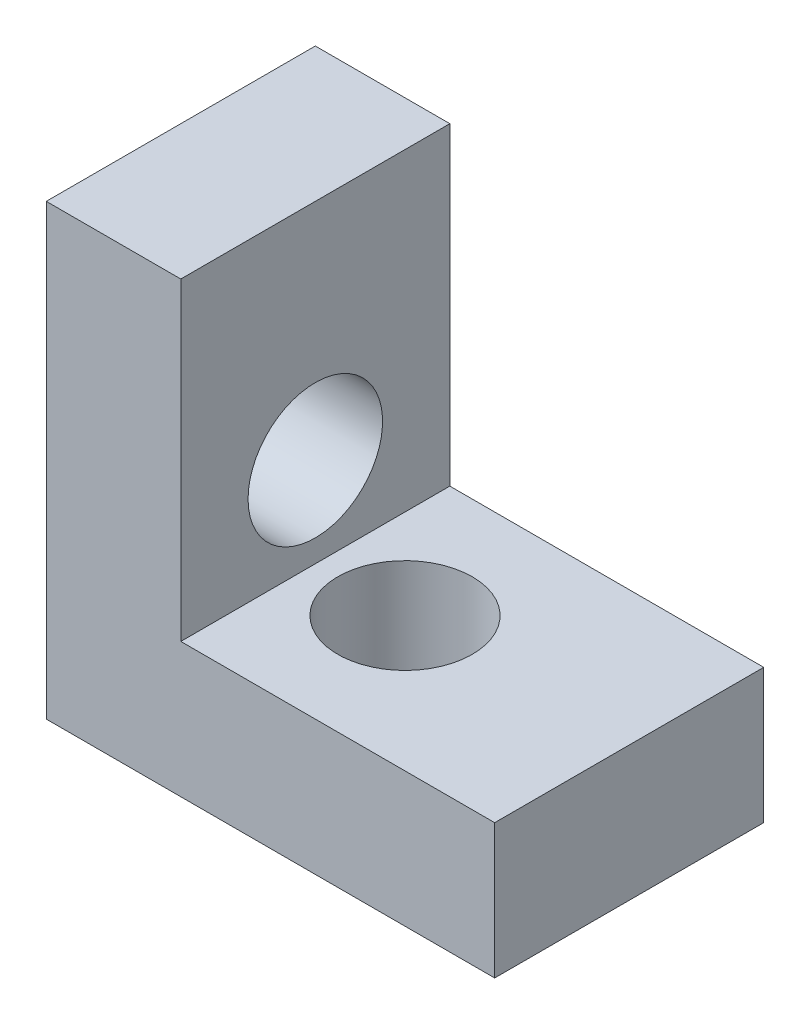
SolidWorks part; units mm, degrees
ref_plane "前视基准面" through (0, 0, 0) normal (0, 0, 1) x (1, 0, 0)
ref_plane "上视基准面" through (0, 0, 0) normal (0, 1, 0) x (1, 0, 0)
ref_plane "右视基准面" through (0, 0, 0) normal (1, 0, 0) x (0, 0, -1)
other "Configuration Table"
sketch "草图1" plane through (0, 0, 0) normal (0, 1, 0) x (1, 0, 0)
  line L1 (-5, -3) -> (5, -3)
  line L2 (-5, -3) -> (-5, 3)
  line L3 (-5, 3) -> (5, 3)
  line L4 (5, -3) -> (5, 3)
  line L5 (-5, -3) -> (5, 3) construction
  line L6 (-5, 3) -> (5, -3) construction
  point P0 (0, 0)
  dimension "D1" = 6
  dimension "D2" = 10
extrude "凸台-拉伸1" add sketch "草图1" along normal blind 3
sketch "草图2" plane through (0, 3, 0) normal (0, 1, 0) x (1, 0, 0)
  line L0 (-5, -3) -> (5, -3) construction
  line L1 (-5, 3) -> (-2, 3)
  line L2 (-5, 3) -> (-5, -3)
  line L3 (-5, -3) -> (-2, -3)
  line L4 (-2, 3) -> (-2, -3)
  dimension "D1" = 3
extrude "凸台-拉伸2" add sketch "草图2" along normal blind 7
sketch "草图3" plane through (0, 0, 0) normal (0, -1, 0) x (1, 0, 0)
  line L4 (5, -3) -> (5, 3)
  line L5 (5, 3) -> (-5, 3)
  line L6 (-5, 3) -> (-5, -3)
  line L7 (-5, -3) -> (5, -3)
  line L8 (5, -3) -> (5, 3) construction
  line L9 (5, 3) -> (-5, 3) construction
  line L10 (-5, 3) -> (-5, -3) construction
  line L11 (-5, -3) -> (5, -3) construction
  circle A0 centre (0, 0) radius 1.5
  point P8 (0.1321, -3)
  dimension "D2" = 3
  dimension "D3" = 5
  dimension "D4" = 3
  dimension "D1" = 0
extrude "切除-拉伸2" cut sketch "草图3" against normal up to surface (3 mm away) up to face at (1.5, 3, 0)
sketch "草图4" plane through (-5, 0, 0) normal (-1, 0, 0) x (0, 0, 1)
  line L0 (-3, 0) -> (3, 0) construction
  line L2 (-3, 10) -> (-3, 0) construction
  circle A0 centre (0, 5) radius 1.5
  point P6 (-3, 4.9345)
  dimension "D1" = 3
  dimension "D2" = 5
  dimension "D3" = 3
extrude "切除-拉伸3" cut sketch "草图4" against normal up to surface (3 mm away) up to face at (-2, 6.5, 0)
